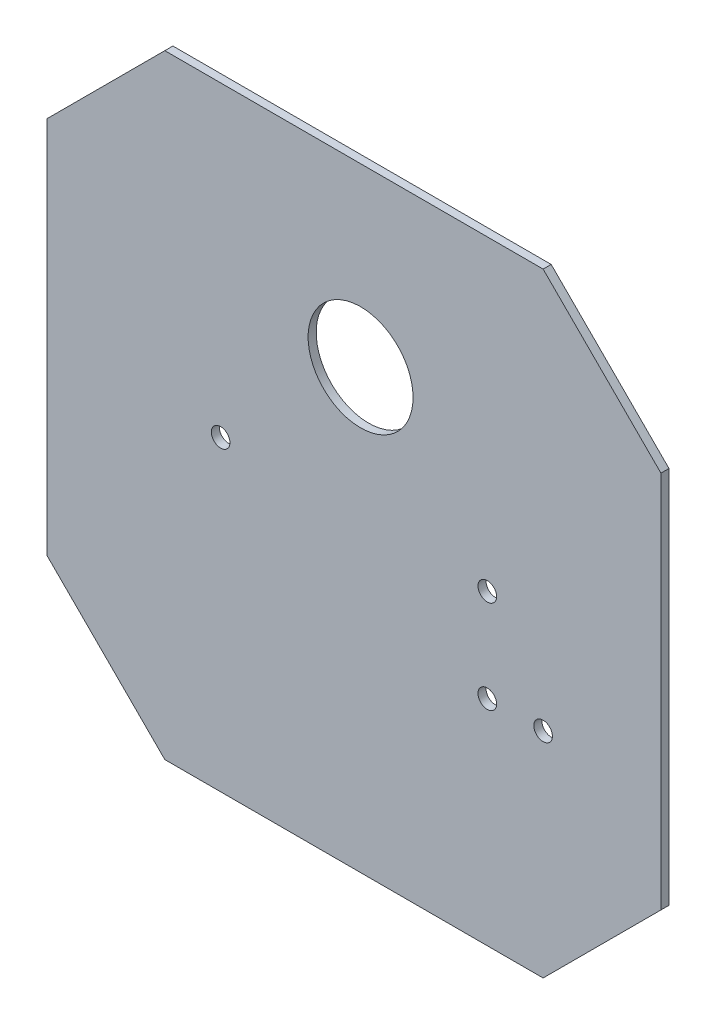
SolidWorks part; units mm, degrees
material "PVC Rigid"
ref_plane "Front Plane" through (0, 0, 0) normal (0, 0, 1) x (1, 0, 0)
ref_plane "Top Plane" through (0, 0, 0) normal (0, 1, 0) x (1, 0, 0)
ref_plane "Right Plane" through (0, 0, 0) normal (1, 0, 0) x (0, 0, -1)
sketch "Sketch1" plane through (0, 0, 0) normal (0, 0, 1) x (1, 0, 0)
  line L0 (-29.649, 62.0347) -> (-29.649, 1.0347)
  line L1 (-10.649, 81.0347) -> (-29.649, 62.0347)
  line L2 (-29.649, 1.0347) -> (-10.649, -17.9653)
  line L3 (50.351, -17.9653) -> (69.351, 1.0347)
  line L4 (69.351, 62.0347) -> (50.351, 81.0347)
  line L5 (-10.649, -17.9653) -> (50.351, -17.9653)
  line L6 (69.351, 1.0347) -> (69.351, 62.0347)
  line L7 (50.351, 81.0347) -> (-10.649, 81.0347)
  circle A0 centre (-1.649, 31.5347) radius 1.5
  circle A1 centre (41.351, 31.5347) radius 1.5
  circle A2 centre (41.351, 16.5347) radius 1.5
  circle A3 centre (50.351, 16.5347) radius 1.5
extrude "Boss-Extrude1" add sketch "Sketch1" along normal blind 1.3
sketch "Sketch3" plane through (0, 0, 1.3) normal (0, 0, 1) x (1, 0, 0)
  circle A0 centre (20.9201, 52.6054) radius 8.4606
extrude "Cut-Extrude1" cut sketch "Sketch3" against normal blind 20
